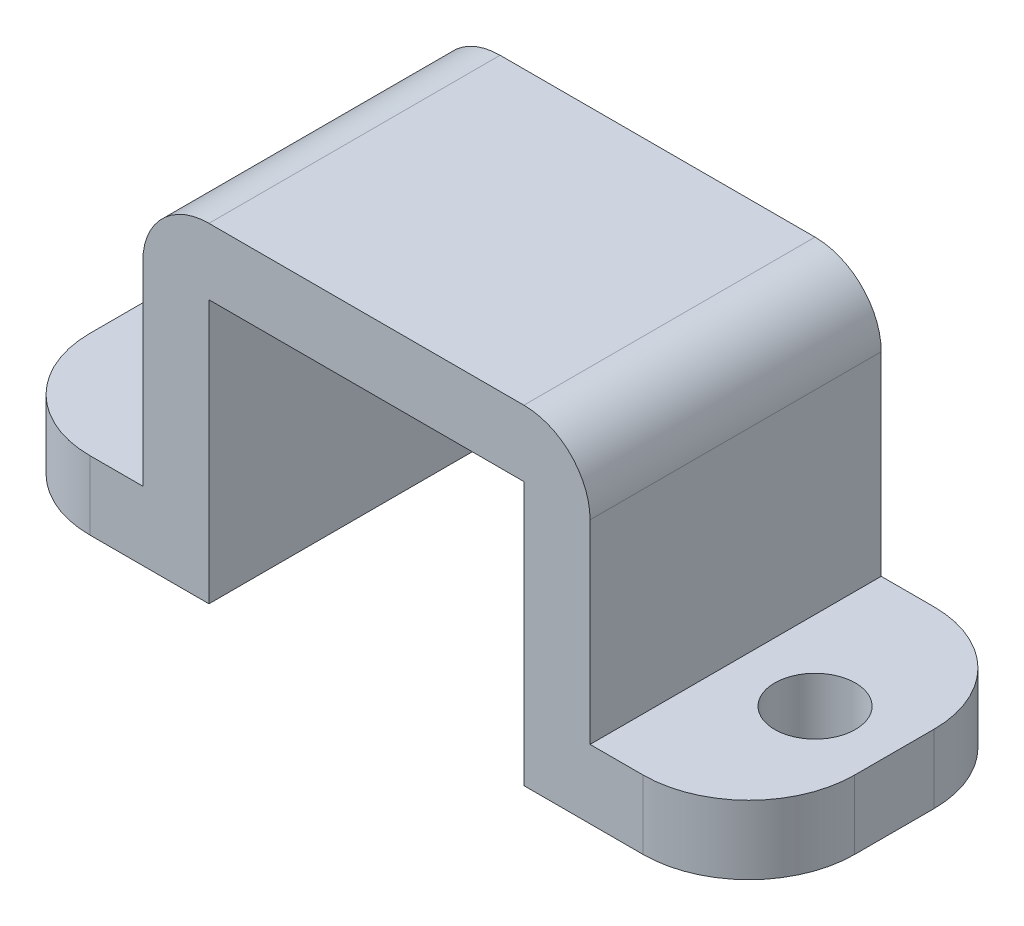
SolidWorks part; units mm, degrees
ref_plane "Front Plane" through (0, 0, 0) normal (0, 0, 1) x (1, 0, 0)
ref_plane "Top Plane" through (0, 0, 0) normal (0, 1, 0) x (1, 0, 0)
ref_plane "Right Plane" through (0, 0, 0) normal (1, 0, 0) x (0, 0, -1)
sketch "Sketch1" plane through (0, 0, 0) normal (0, 0, 1) x (1, 0, 0)
  line L0 (0, 0) -> (0, 9.95) construction
  line L1 (-5.95, 0) -> (-5.95, 9.95)
  line L2 (-5.95, 9.95) -> (5.95, 9.95)
  line L4 (8.45, 12.45) -> (-8.45, 12.45)
  line L5 (-8.45, 12.45) -> (-8.45, 2.6)
  line L6 (-8.6587, 0) -> (-5.95, 0)
  line L7 (14.45, 0) -> (14.45, 2.6)
  line L8 (-8.6587, 0) -> (-14.45, 0)
  line L10 (-8.45, 2.6) -> (-14.45, 2.6)
  line L11 (-14.45, 0) -> (-14.45, 2.6)
  line L12 (8.45, 2.6) -> (14.45, 2.6)
  line L13 (8.6587, 0) -> (14.45, 0)
  line L14 (8.6587, 0) -> (5.95, 0)
  line L15 (8.45, 12.45) -> (8.45, 2.6)
  line L16 (5.95, 0) -> (5.95, 9.95)
  line L17 (0, 12.45) -> (0, 11.3048) construction
  dimension "D1" = 5.95
  dimension "D2" = 9.95
  dimension "D3" = 2.5
  dimension "D4" = 2.5
  dimension "D5" = 2.6
  dimension "D6" = 6
extrude "Boss-Extrude1" add sketch "Sketch1" along normal blind 11
fillet "Fillet1" radius 4 4 edges at (14.45, 1.3, 0) (14.45, 1.3, 11) (-14.45, 1.3, 0) (-14.45, 1.3, 11)
fillet "Fillet2" radius 2.5 2 edges at (8.45, 12.45, 5.5) (-8.45, 12.45, 5.5)
sketch "Sketch2" plane through (0, 2.6, 0) normal (0, 1, 0) x (1, 0, 0)
  line L0 (-14.45, -7) -> (-14.45, -4) construction
  line L1 (14.45, -7) -> (14.45, -4) construction
  circle A0 centre (-11.45, -5.5) radius 1.525
  circle A1 centre (11.45, -5.5) radius 1.525
  dimension "D2" = 3.05
  dimension "D4" = 3.05
  dimension "D1" = 3
  dimension "D3" = 3
extrude "Cut-Extrude1" cut sketch "Sketch2" against normal blind 11
